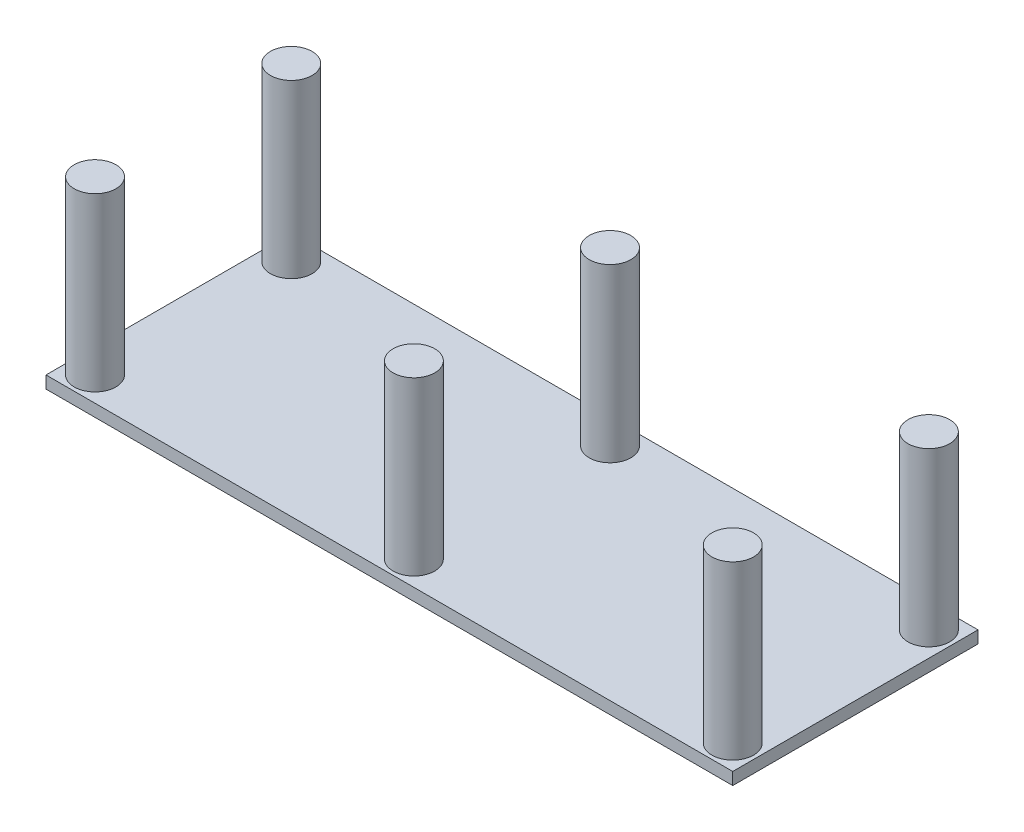
SolidWorks part; units mm, degrees
ref_plane "Ön Düzlem" through (0, 0, 0) normal (0, 0, 1) x (1, 0, 0)
ref_plane "Üst Düzlem" through (0, 0, 0) normal (0, 1, 0) x (1, 0, 0)
ref_plane "Sağ Düzlem" through (0, 0, 0) normal (1, 0, 0) x (0, 0, -1)
sketch "Çizim1" plane through (0, 0, 0) normal (0, 1, 0) x (1, 0, 0)
  line L0 (-20, 80) -> (260, 80)
  line L2 (0, 0) -> (0, 60)
  line L3 (0, 60) -> (240, 60)
  line L4 (240, 0) -> (240, 60)
  line L5 (260, -20) -> (260, 80)
  line L6 (-20, -20) -> (260, -20)
  line L7 (-20, -20) -> (-20, 80)
  line L8 (0, 60) -> (-20, 80) construction
  line L9 (-10, 70) -> (260, 70) construction
  line L10 (120, 80) -> (120, -20) construction
  line L11 (-20, 30) -> (260, 30) construction
  line L12 (0, 0) -> (240, 0) construction
  circle A0 centre (-10, 70) radius 8.5
  circle A1 centre (-10, -10) radius 8.5
  circle A2 centre (250, 70) radius 8.5
  circle A3 centre (250, -10) radius 8.5
  dimension "D4" = 17
  dimension "D1" = 60
  dimension "D2" = 240
  dimension "D3" = 20
extrude "Yükseklik-Ekstrüzyon6" add sketch "Çizim1" along normal blind 5
sketch "Çizim16" plane through (0, 5, 0) normal (0, 1, 0) x (1, 0, 0)
  circle A0 centre (-10, 70) radius 8.5
  circle A1 centre (-10, -10) radius 8.5
  circle A2 centre (250, 69.9664) radius 8.5
  circle A3 centre (250, -10) radius 8.5
  circle A4 centre (120, 69.9664) radius 8.5
  circle A5 centre (120, -10) radius 8.5
extrude "Yükseklik-Ekstrüzyon7" add sketch "Çizim16" along normal blind 70
